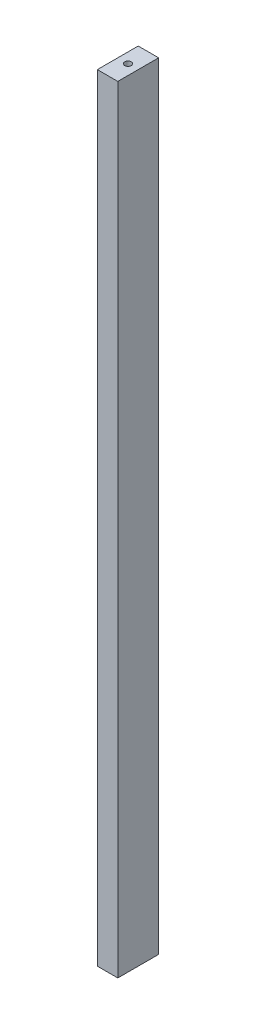
SolidWorks part; units mm, degrees
ref_plane "Спереди" through (0, 0, 0) normal (0, 0, 1) x (1, 0, 0)
ref_plane "Сверху" through (0, 0, 0) normal (0, 1, 0) x (1, 0, 0)
ref_plane "Справа" through (0, 0, 0) normal (1, 0, 0) x (0, 0, -1)
other "Configuration Table"
sketch "Эскиз1" plane through (0, 0, 0) normal (0, 1, 0) x (1, 0, 0)
  line L1 (12.5, 25) -> (-12.5, 25)
  line L2 (12.5, 25) -> (12.5, -25)
  line L3 (12.5, -25) -> (-12.5, -25)
  line L4 (-12.5, 25) -> (-12.5, -25)
  line L5 (12.5, 25) -> (-12.5, -25) construction
  line L6 (12.5, -25) -> (-12.5, 25) construction
  point P0 (0, 0)
extrude "Бобышка-Вытянуть1" add sketch "Эскиз1" along normal blind 950
sketch "Эскиз2" plane through (0, 0, 0) normal (0, -1, 0) x (1, 0, 0)
  circle A0 centre (0, 0) radius 4
extrude "Вырез-Вытянуть1" cut sketch "Эскиз2" against normal blind 50
sketch "Эскиз3" plane through (0, 950, 0) normal (0, 1, 0) x (1, 0, 0)
  circle A0 centre (0, 0) radius 4
extrude "Вырез-Вытянуть2" cut sketch "Эскиз3" against normal blind 50
